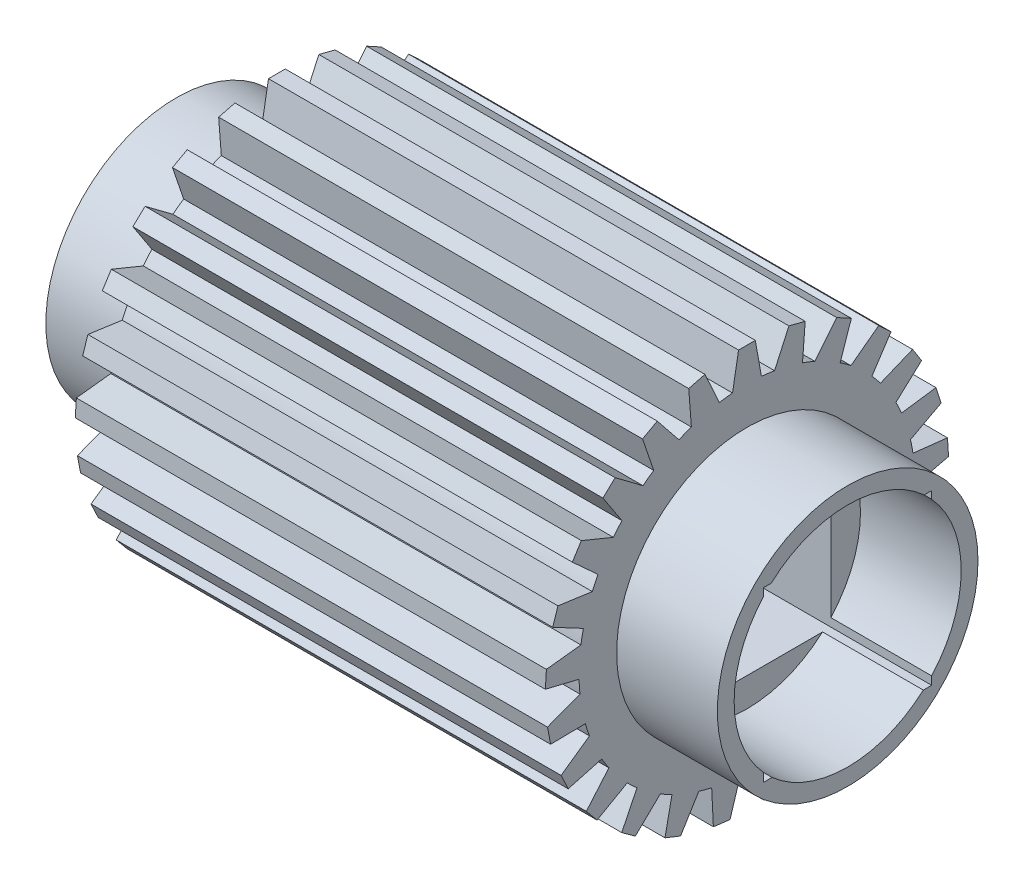
SolidWorks part; units mm, degrees
ref_plane "Front Plane" through (0, 0, 0) normal (0, 0, 1) x (1, 0, 0)
ref_plane "Top Plane" through (0, 0, 0) normal (0, 1, 0) x (1, 0, 0)
ref_plane "Right Plane" through (0, 0, 0) normal (1, 0, 0) x (0, 0, -1)
sketch "Sketch2" plane through (0, 0, 0) normal (1, 0, 0) x (0, 0, -1)
  line L0 (0, 5) -> (0, 6) construction
  line L1 (-0.25, 6) -> (0.25, 6)
  line L2 (-0.25, 6) -> (-0.7008, 3.4435)
  line L3 (-0.7008, 3.4435) -> (0.7008, 3.4435)
  line L4 (0.7008, 3.4435) -> (0.25, 6)
  line L5 (0, 5) -> (0, 3.4435) construction
  arc A0 (0.4296, 4.9815) -> (-0.4296, 4.9815) centre (0, 0) ccw
  point P8 (0, 6)
  dimension "D1" = 10
  dimension "D2" = 1
  dimension "D3" = 0.5
  dimension "D4" = 100
extrude "Boss-Extrude2" add sketch "Sketch2" along normal blind 5 and the other way blind 9 contours L4 A0 L2 L3 | A0 L4 L1 L2
sketch "Sketch3" plane through (0, 0, 0) normal (1, 0, 0) x (0, 0, -1)
  circle A0 centre (0, 0) radius 5
  dimension "D1" = 10
extrude "Boss-Extrude3" add sketch "Sketch3" along normal blind 5 and the other way blind 9
pattern_circular "CirPattern1" count 25 over 360 about axis through (0, 0, 0) along (1, 0, 0) of "Boss-Extrude2"
sketch "Sketch4" plane through (5, 0, 0) normal (1, 0, 0) x (0, 0, -1)
  line L1 (-2.5, -2.5) -> (2.5, -2.5)
  line L2 (-2.5, -2.5) -> (-2.5, 2.5)
  line L3 (-2.5, 2.5) -> (2.5, 2.5)
  line L4 (2.5, -2.5) -> (2.5, 2.5)
  dimension "D1" = 2.5
  dimension "D2" = 5
  dimension "D3" = 5
  dimension "D4" = 2.5
extrude "Cut-Extrude1" cut sketch "Sketch4" against normal blind 18
sketch "Sketch5" plane through (5, 0, 0) normal (1, 0, 0) x (0, 0, -1)
  line L1 (0, -5) -> (0, -6.0359) construction
  circle A0 centre (0, 0) radius 5.5
  arc A1 (-0.1981, -4.9961) -> (0.1981, -4.9961) centre (0, 0) ccw construction
  dimension "D1" = 11
sketch "Sketch6" plane through (5, 0, 0) normal (1, 0, 0) x (0, 0, -1)
  circle A0 centre (0, 0) radius 3.8814
  circle A1 centre (0, 0) radius 3.3814
  circle A2 centre (0, 0) radius 3.8814 construction
  dimension "D1" = 0.5
  dimension "D2" = 0
extrude "Boss-Extrude4" add sketch "Sketch6" along normal blind 3 and the other way blind 17
sketch "Sketch7" plane through (5, 0, 0) normal (1, 0, 0) x (0, 0, -1)
  line L0 (-2.5, 2.2769) -> (-2.5, -2.2769) construction
  line L1 (-2.5, 2.5) -> (2.5, 2.5)
  line L2 (-2.5, 2.5) -> (-2.5, -2.5216)
  line L3 (-2.5, -2.5216) -> (2.5, -2.5216)
  line L4 (2.5, 2.5) -> (2.5, -2.5216)
  line L5 (2.5, -2.2769) -> (2.5, 2.2769) construction
  line L6 (2.2769, 2.5) -> (-2.2769, 2.5) construction
  dimension "D1" = 0
  dimension "D2" = 0
extrude "Cut-Extrude2" cut sketch "Sketch7" against normal blind 20 and the other way blind 10
